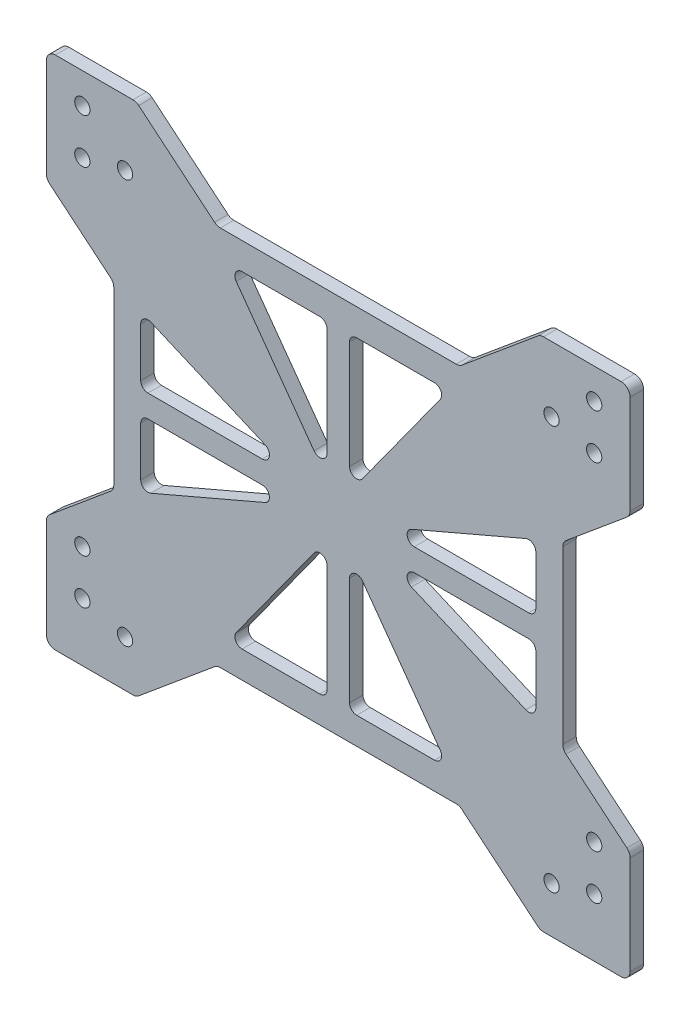
SolidWorks part; units mm, degrees
material "黑板"
ref_plane "前视基准面" through (0, 0, 0) normal (0, 0, 1) x (1, 0, 0)
ref_plane "上视基准面" through (0, 0, 0) normal (0, 1, 0) x (1, 0, 0)
ref_plane "右视基准面" through (0, 0, 0) normal (1, 0, 0) x (0, 0, -1)
sketch "草图1" plane through (0, 0, 0) normal (0, 0, 1) x (1, 0, 0)
  line L1 (-65, 57.4) -> (65, 57.4)
  line L2 (-65, 57.4) -> (-65, -57.4)
  line L3 (-65, -57.4) -> (65, -57.4)
  line L4 (65, 57.4) -> (65, -57.4)
  line L5 (-65, 57.4) -> (65, -57.4) construction
  line L6 (-65, -57.4) -> (65, 57.4) construction
  point P0 (0, 0)
  dimension "D1" = 130
  dimension "D2" = 114.8
extrude "凸台-拉伸1" add sketch "草图1" along normal blind 3
sketch "草图2" plane through (0, 0, 0) normal (0, 0, -1) x (-1, 0, 0)
  line L0 (0, 0) -> (87.7551, 0) construction
  line L1 (0, 0) -> (0, 41.3739) construction
  circle A1 centre (57, -34.4) radius 1.7
  circle A3 centre (57, -44.4) radius 1.7
  circle A9 centre (57, 50.6) radius 1.7
  circle A11 centre (57, 40.6) radius 1.7
  circle A12 centre (-57, -44.4) radius 1.7
  circle A13 centre (-57, -34.4) radius 1.7
  circle A14 centre (-57, 40.6) radius 1.7
  circle A15 centre (-57, 50.6) radius 1.7
  dimension "D1" = 3.4
extrude "切除-拉伸1" cut sketch "草图2" against normal through all
sketch "草图4" plane through (0, 0, 0) normal (0, 0, -1) x (-1, 0, 0)
  line L1 (-47.5, 42.9) -> (47.5, 42.9) construction
  line L2 (-47.5, 42.9) -> (-47.5, -47.1) construction
  line L3 (-47.5, -47.1) -> (47.5, -47.1) construction
  line L4 (47.5, 42.9) -> (47.5, -47.1) construction
  circle A6 centre (-47.5, 42.9) radius 1.7
  circle A7 centre (47.5, 42.9) radius 1.7
  circle A8 centre (47.5, -47.1) radius 1.7
  circle A9 centre (-47.5, -47.1) radius 1.7
  dimension "D5" = 3.4
  dimension "D1" = 95
  dimension "D2" = 90
  dimension "D3" = 42.9
  dimension "D4" = 47.5
extrude "切除-拉伸3" cut sketch "草图4" against normal through all
sketch "草图7" plane through (0, 0, 0) normal (0, 0, -1) x (-1, 0, 0)
  line L0 (-65, 32.5) -> (-50, 20)
  line L1 (-65, -57.4) -> (-65, 57.4) construction
  line L2 (-50, 20) -> (-50, -20)
  line L3 (-50, -20) -> (-65, -32.5)
  line L4 (-65, -32.5) -> (-65, 32.5)
  line L5 (-65, 0) -> (-50, 0) construction
  line L6 (-50, 0) -> (0, 0) construction
  line L7 (0, 0) -> (0, 23.889) construction
  line L8 (50, -20) -> (65, -32.5)
  line L9 (50, 20) -> (50, -20)
  line L10 (65, 32.5) -> (50, 20)
  line L11 (65, -32.5) -> (65, 32.5)
  line L12 (-45, -57.4) -> (45, -57.4)
  line L13 (65, -57.4) -> (-65, -57.4) construction
  line L14 (45, -57.4) -> (27, -42.4)
  line L15 (27, -42.4) -> (-27, -42.4)
  line L16 (-27, -42.4) -> (-45, -57.4)
  line L17 (0, -57.4) -> (0, -42.4) construction
  line L18 (0, -42.4) -> (0, 0) construction
  line L19 (-45, -57.4) -> (-65, -57.4) construction
  line L20 (27, 42.4) -> (-27, 42.4)
  line L21 (45, 57.4) -> (27, 42.4)
  line L22 (-45, 57.4) -> (45, 57.4)
  line L23 (-27, 42.4) -> (-45, 57.4)
  dimension "D1" = 65
  dimension "D2" = 40
  dimension "D3" = 15
  dimension "D4" = 15
  dimension "D5" = 90
extrude "切除-拉伸5" cut sketch "草图7" against normal through all
sketch "草图8" plane through (0, 0, 0) normal (0, 0, -1) x (-1, 0, 0)
  line L2 (-50, 20) -> (-27, 42.4) construction
  line L3 (27, 42.4) -> (50, 20) construction
  line L12 (-27, 42.4) -> (27, 42.4) construction
  line L13 (-27, 42.4) -> (27, 42.4) construction
  line L14 (50, -20) -> (27, -42.4) construction
  line L15 (50, 20) -> (50, -20) construction
  line L20 (-27, -42.4) -> (-50, -20) construction
  line L29 (50, 20) -> (50, -20) construction
  line L30 (27, -42.4) -> (-27, -42.4) construction
  line L31 (27, -42.4) -> (-27, -42.4) construction
  line L32 (-50, -20) -> (-50, 20) construction
  line L33 (-50, -20) -> (-50, 20) construction
  line L34 (-44, 17.4681) -> (-24.561, 36.4)
  line L35 (-24.561, 36.4) -> (24.561, 36.4)
  line L36 (24.561, 36.4) -> (44, 17.4681)
  line L37 (44, 17.4681) -> (44, -17.4681)
  line L38 (44, -17.4681) -> (24.561, -36.4)
  line L39 (24.561, -36.4) -> (-24.561, -36.4)
  line L40 (-24.561, -36.4) -> (-44, -17.4681)
  line L41 (-44, -17.4681) -> (-44, 17.4681)
  dimension "D1" = 6
extrude "切除-拉伸6" cut sketch "草图8" against normal through all
sketch "草图9" plane through (0, 0, 0) normal (0, 0, -1) x (-1, 0, 0)
  line L0 (-44, 17.4681) -> (-1, -1)
  line L1 (-1, -1) -> (24.561, -36.4)
  line L2 (-24.561, 36.4) -> (1, 1)
  line L3 (1, 1) -> (44, -17.4681)
  line L4 (-44, -17.4681) -> (-1, 1)
  line L5 (-1, 1) -> (24.561, 36.4)
  line L6 (44, 17.4681) -> (1, -1)
  line L7 (1, -1) -> (-24.561, -36.4)
  line L8 (-1, -1) -> (1, -1) construction
  line L9 (-1, 1) -> (-1, -1) construction
  line L10 (1, -1) -> (1, 1)
  line L11 (-1, 1) -> (1, 1)
  line L12 (-1, 1) -> (1, -1) construction
  line L13 (34.2805, 26.9341) -> (-34.2805, -26.9341) construction
  line L14 (44, 17.4681) -> (24.561, 36.4) construction
  line L15 (-44, -17.4681) -> (-24.561, -36.4) construction
  line L16 (34.2805, -26.9341) -> (-34.2805, 26.9341) construction
  line L17 (24.561, -36.4) -> (44, -17.4681) construction
  line L18 (-24.561, 36.4) -> (-44, 17.4681) construction
  line L19 (-44, 17.4681) -> (-24.561, 36.4)
  line L20 (24.561, 36.4) -> (44, 17.4681)
  dimension "D1" = 2
extrude "凸台-拉伸4" add sketch "草图9" against normal through all
sketch "草图10" plane through (0, 0, 0) normal (0, 0, -1) x (-1, 0, 0)
  line L0 (-44, 0) -> (44, 0)
  line L1 (-44, 17.4681) -> (-44, -17.4681) construction
  line L2 (44, -17.4681) -> (44, 17.4681) construction
  line L3 (0, 36.4) -> (0, -36.4)
  line L4 (24.561, 36.4) -> (-24.561, 36.4) construction
  line L5 (-24.561, -36.4) -> (24.561, -36.4) construction
extrude "拉伸-薄壁1" add sketch "草图10" against normal through all thin thin type mid plane wall 5
fillet "圆角2" radius 1.6 24 edges at (2.5, -36.4, 1.5) (24.561, -36.4, 1.5) (2.5, -5.8472, 1.5) (-24.561, -36.4, 1.5) (-2.5, -36.4, 1.5) (-2.5, -5.8472, 1.5) (-44, 17.4681, 1.5) (-44, 2.5, 1.5) (-9.1492, 2.5, 1.5) (-44, -2.5, 1.5) (-44, -17.4681, 1.5) (-9.1492, -2.5, 1.5) (24.561, 36.4, 1.5) (2.5, 36.4, 1.5) (2.5, 5.8472, 1.5) (-2.5, 5.8472, 1.5) (44, 2.5, 1.5) (44, 17.4681, 1.5) (9.1492, 2.5, 1.5) (44, -17.4681, 1.5) (44, -2.5, 1.5) (9.1492, -2.5, 1.5) (-2.5, 36.4, 1.5) (-24.561, 36.4, 1.5)
fillet "圆角3" radius 2 20 edges at (50, 20, 1.5) (50, -20, 1.5) (65, -32.5, 1.5) (65, -57.4, 1.5) (45, -57.4, 1.5) (27, -42.4, 1.5) (-27, -42.4, 1.5) (-45, -57.4, 1.5) (-65, -57.4, 1.5) (-65, -32.5, 1.5) (-50, -20, 1.5) (-65, 57.4, 1.5) (-45, 57.4, 1.5) (-27, 42.4, 1.5) (27, 42.4, 1.5) (45, 57.4, 1.5) (65, 57.4, 1.5) (65, 32.5, 1.5) (-50, 20, 1.5) (-65, 32.5, 1.5)
